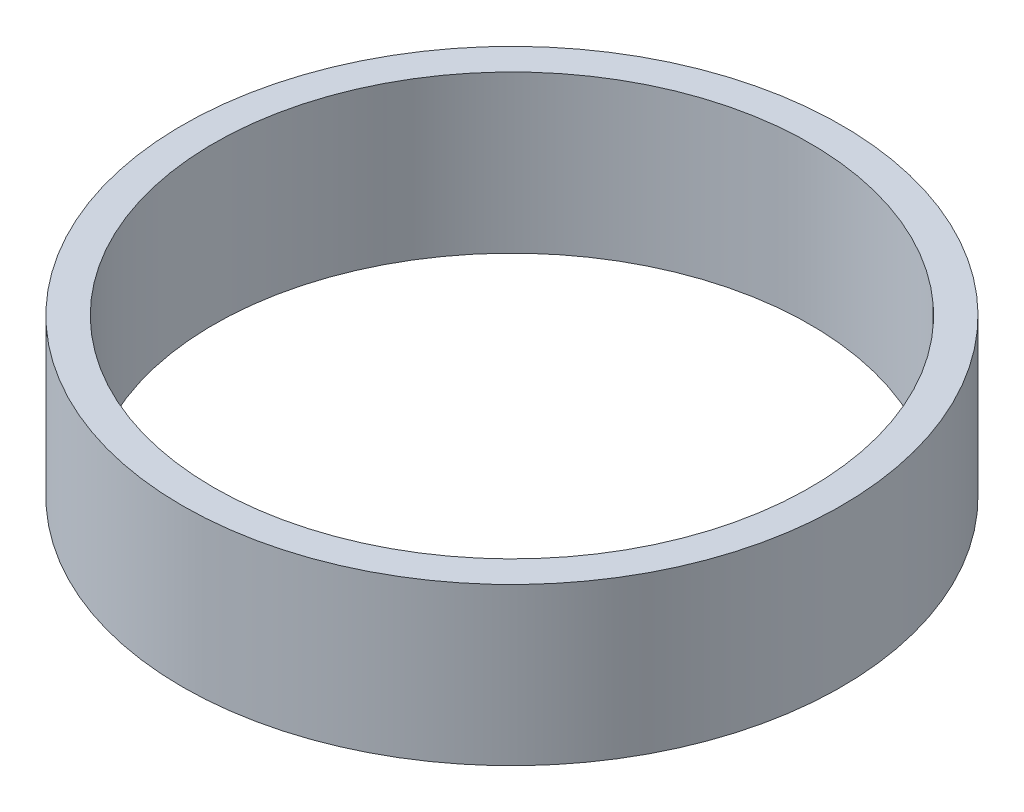
SolidWorks part; units mm, degrees
ref_plane "Front Plane" through (0, 0, 0) normal (0, 0, 1) x (1, 0, 0)
ref_plane "Top Plane" through (0, 0, 0) normal (0, 1, 0) x (1, 0, 0)
ref_plane "Right Plane" through (0, 0, 0) normal (1, 0, 0) x (0, 0, -1)
sketch "Sketch1" plane through (0, 0, 0) normal (0, 1, 0) x (1, 0, 0)
  circle A0 centre (0, 0) radius 21
  circle A1 centre (0, 0) radius 19
  dimension "D1" = 42
  dimension "D2" = 38
extrude "Boss-Extrude2" add sketch "Sketch1" along normal blind 1
sketch "Sketch2" plane through (0, 1, 0) normal (0, 1, 0) x (1, 0, 0)
  circle A0 centre (0, 0) radius 21
  circle A1 centre (0, 0) radius 19
  dimension "D1" = 42
  dimension "D2" = 38
extrude "Boss-Extrude3" add sketch "Sketch2" along normal blind 9
